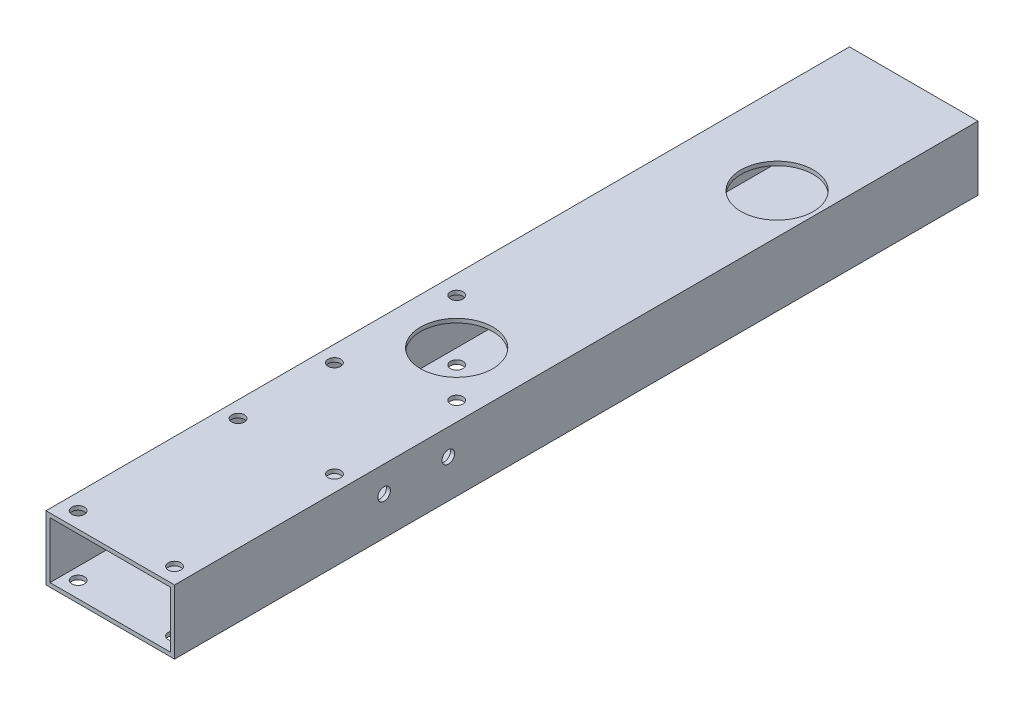
SolidWorks part; units mm, degrees
material "6061 Alloy"
ref_plane "Front Plane" through (0, 0, 0) normal (0, 0, 1) x (1, 0, 0)
ref_plane "Top Plane" through (0, 0, 0) normal (0, 1, 0) x (1, 0, 0)
ref_plane "Right Plane" through (0, 0, 0) normal (1, 0, 0) x (0, 0, -1)
sketch "Sketch1" plane through (0, 0, 0) normal (0, 0, 1) x (1, 0, 0)
  line L0 (-23.8125, 11.1125) -> (23.8125, 11.1125)
  line L2 (-25.4, 12.7) -> (25.4, 12.7)
  line L3 (-25.4, 12.7) -> (-25.4, -12.7)
  line L4 (-25.4, -12.7) -> (25.4, -12.7)
  line L5 (25.4, 12.7) -> (25.4, -12.7)
  line L10 (23.8125, 11.1125) -> (23.8125, -11.1125)
  line L11 (-23.8125, -11.1125) -> (23.8125, -11.1125)
  line L12 (-23.8125, 11.1125) -> (-23.8125, -11.1125)
  point P12 (0, 12.7)
  point P14 (25.4, 0)
  dimension "Wall Thickness" = 1.5875
  dimension "Outside Width" = 50.8
  dimension "Outside Height" = 25.4
  dimension "Inside Height" = 22.225
  dimension "Inside Width" = 47.625
sketch "Sketch2" plane through (0, 0, 0) normal (1, 0, 0) x (0, 0, -1)
  line L0 (158.75, 0) -> (-158.75, 0)
  point P4 (0, 0)
  point P7 (-158.75, 0)
  point P10 (158.75, 0)
  dimension "Length" = 317.5
sketch "Sketch3" plane through (0, 0, 0) normal (0, 0, 1) x (1, 0, 0)
  line L21 (25.4, 12.7) -> (-25.4, 12.7)
  line L22 (25.4, -12.7) -> (25.4, 12.7)
  line L23 (-25.4, -12.7) -> (25.4, -12.7)
  line L24 (-25.4, 12.7) -> (-25.4, -12.7)
  line L25 (25.4, 12.7) -> (-25.4, 12.7)
  line L26 (25.4, -12.7) -> (25.4, 12.7)
  line L27 (-25.4, -12.7) -> (25.4, -12.7)
  line L28 (-25.4, 12.7) -> (-25.4, -12.7)
  line L29 (23.8125, 11.1125) -> (-23.8125, 11.1125)
  line L30 (23.8125, -11.1125) -> (23.8125, 11.1125)
  line L31 (-23.8125, -11.1125) -> (23.8125, -11.1125)
  line L32 (-23.8125, 11.1125) -> (-23.8125, -11.1125)
  line L33 (23.8125, 11.1125) -> (-23.8125, 11.1125)
  line L34 (23.8125, -11.1125) -> (23.8125, 11.1125)
  line L35 (-23.8125, -11.1125) -> (23.8125, -11.1125)
  line L36 (-23.8125, 11.1125) -> (-23.8125, -11.1125)
  dimension "D1" = 0
  dimension "D2" = 0
extrude "Boss-Extrude1" add sketch "Sketch3" along normal up to vertex (158.75 mm away) and the other way up to vertex (158.75 mm away) up to point (0, 0, 158.75) other way up to point (0, 0, -158.75)
sketch "Drawing Reference" plane through (0, 0, 0) normal (1, 0, 0) x (0, 0, -1)
  line L0 (-158.75, 0) -> (158.75, 0) construction
  line L1 (0, -12.7) -> (0, 12.7) construction
  line L2 (-158.75, -12.7) -> (158.75, -12.7) construction
  line L5 (-158.75, 12.7) -> (158.75, 12.7) construction
  point P7 (-122.174, 0)
  point P8 (122.174, 0)
  dimension "D1" = 36.576
sketch "Sketch4" plane through (0, 12.7, 0) normal (0, 1, 0) x (1, 0, 0)
  line L0 (0, 158.75) -> (0, 95.25) construction
  line L1 (25.4, 158.75) -> (-25.4, 158.75) construction
  line L2 (0, 95.25) -> (9.525, 95.25) construction
  line L3 (0, 158.75) -> (0, -26.67) construction
  circle A1 centre (9.525, 95.25) radius 14.2875
  circle A3 centre (9.525, 95.25) radius 117.5004 construction
  circle A4 centre (0, -21.8637) radius 14.2875
  dimension "D1" = 63.5
  dimension "D3" = 235.0008
  dimension "D2" = 9.525
extrude "Cut-Extrude1" cut sketch "Sketch4" against normal blind 39.37
sketch "Sketch6" plane through (0, 12.7, 0) normal (0, 1, 0) x (1, 0, 0)
  line L0 (-17.9605, -3.9032) -> (17.9605, -39.8242) construction
  circle A0 centre (0, -21.8637) radius 25.4 construction
  point P8 (0, -21.8637)
  dimension "D1" = 50.8
hole_wizard "#10 Clearance Hole1" positions "Sketch7" profile "Sketch8" hole size "#10" standard "ANSI Inch" end condition through all
sketch "Sketch7" plane through (0, 12.7, 0) normal (0, 1, 0) x (1, 0, 0)
  point P0 (-17.9605, -3.9032)
  point P3 (17.9605, -39.8242)
sketch "Sketch8" plane through (-17.9605, 12.7, 3.9032) normal (1, 0, 0) x (0, 0, 1)
  line L0 (0, 0) -> (0, 25.4)
  line L1 (0, 25.4) -> (2.4892, 25.4)
  line L2 (2.4892, 25.4) -> (2.4892, 0)
  line L5 (2.4892, 0) -> (0, 0)
  line L11 (0, -6.35) -> (0, 107.95) construction
  dimension "Thru Hole Dia." = 4.9784
  dimension "Thru Hole Depth" = 25.4
sketch "Sketch9" plane through (-25.4, 0, 0) normal (-1, 0, 0) x (0, 0, 1)
  line L0 (75.9497, 2.425) -> (50.5497, 2.425) construction
hole_wizard "#10 Clearance Hole2" positions "Sketch12" profile "Sketch13" hole size "#10" standard "ANSI Inch" end condition through all
sketch "Sketch12" plane through (-25.4, 0, 0) normal (-1, 0, 0) x (0, 0, 1)
  point P0 (50.5497, 2.425)
  point P3 (75.9497, 2.425)
sketch "Sketch13" plane through (-25.4, 2.425, 50.5497) normal (0, 1, 0) x (0, 0, 1)
  line L0 (0, 0) -> (0, 50.8)
  line L1 (0, 50.8) -> (2.4892, 50.8)
  line L2 (2.4892, 50.8) -> (2.4892, 0)
  line L5 (2.4892, 0) -> (0, 0)
  line L11 (0, -6.35) -> (0, 107.95) construction
  dimension "Thru Hole Dia." = 4.9784
  dimension "Thru Hole Depth" = 50.8
hole_wizard "#10 Clearance Hole3" positions "Sketch14" profile "Sketch15" hole size "#10" standard "ANSI Inch" end condition through all
sketch "Sketch14" plane through (0, 12.7, 0) normal (0, 1, 0) x (1, 0, 0)
  point P0 (-19.05, -51.1131)
  point P3 (-19.05, -89.2131)
  point P6 (19.05, -89.2131)
  point P9 (19.05, -152.4)
  point P12 (-19.05, -152.4)
sketch "Sketch15" plane through (-19.05, 12.7, 51.1131) normal (1, 0, 0) x (0, 0, 1)
  line L0 (0, 0) -> (0, 25.4)
  line L1 (0, 25.4) -> (2.4892, 25.4)
  line L2 (2.4892, 25.4) -> (2.4892, 0)
  line L5 (2.4892, 0) -> (0, 0)
  line L11 (0, -6.35) -> (0, 107.95) construction
  dimension "Thru Hole Dia." = 4.9784
  dimension "Thru Hole Depth" = 25.4
equation "\"D1@Drawing Reference\"=\"Outside Width@Sketch1\" * 0.72"
